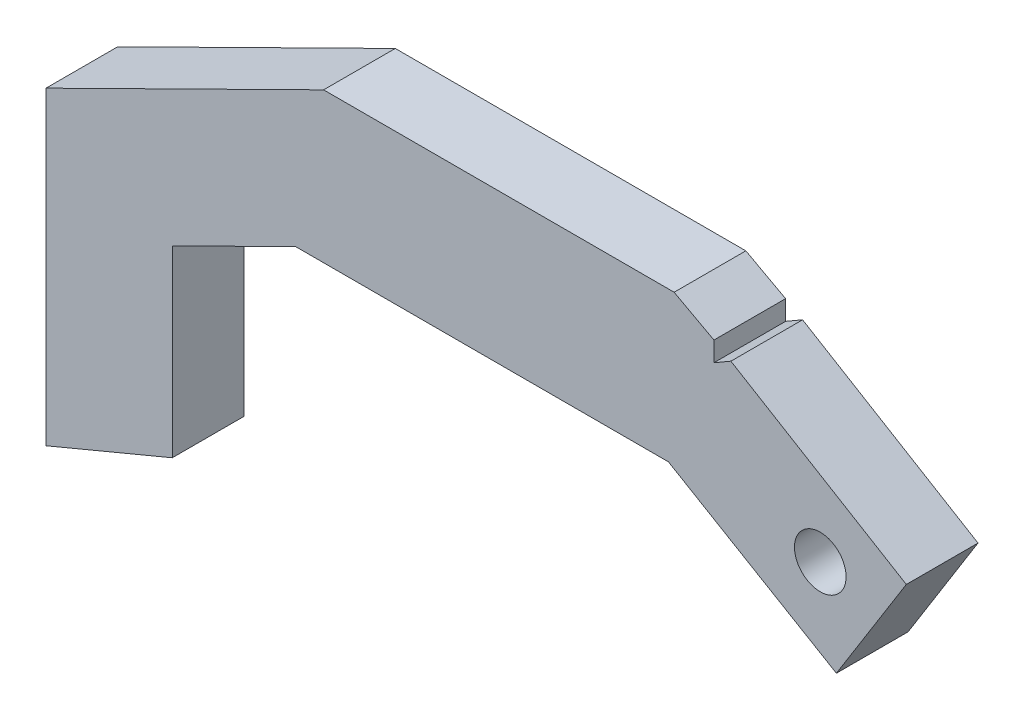
SolidWorks part; units mm, degrees
ref_plane "Front Plane" through (0, 0, 0) normal (0, 0, 1) x (1, 0, 0)
ref_plane "Top Plane" through (0, 0, 0) normal (0, 1, 0) x (1, 0, 0)
ref_plane "Right Plane" through (0, 0, 0) normal (1, 0, 0) x (0, 0, -1)
sketch "Sketch2" plane through (0, 0, 0) normal (0, 0, 1) x (1, 0, 0)
  line L9 (-15.6495, -2.7546) -> (-13.8882, -3.7075)
  line L15 (-13.8882, -3.7075) -> (-13.8882, -4.5784)
  line L23 (-15.6495, -2.7546) -> (-31.174, -2.7546)
  line L24 (-31.174, -2.7546) -> (-43.4678, -8.8368)
  line L25 (-43.4678, -8.8368) -> (-43.4678, -22.5528)
  line L26 (-43.4678, -22.5528) -> (-37.8757, -20.2178)
  line L27 (-37.8757, -20.2178) -> (-37.8757, -12.0898)
  line L28 (-37.8757, -12.0898) -> (-32.4118, -9.3866)
  line L29 (-32.4118, -9.3866) -> (-15.9018, -9.3866)
  line L30 (-15.9018, -9.3866) -> (-8.464, -13.7752)
  line L31 (-8.464, -13.7752) -> (-5.3678, -8.8211)
  line L32 (-13.8882, -4.5784) -> (-13.1361, -4.1429)
  line L33 (-13.1361, -4.1429) -> (-5.3678, -8.8211)
  circle A1 centre (-9.1778, -9.8651) radius 1.143
  dimension "D10" = 8.128
  dimension "D11" = 13.716
  dimension "D12" = 6.096
  dimension "D13" = 16.51
  dimension "D14" = 8.636
extrude "Boss-Extrude1" add sketch "Sketch2" along normal blind 3.175
